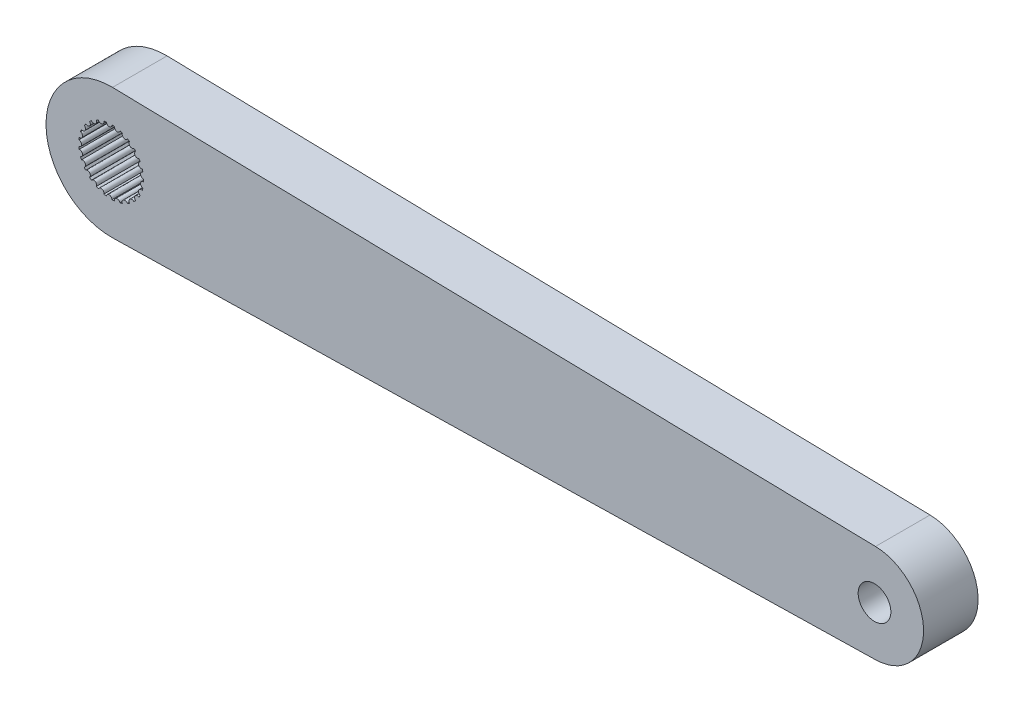
SolidWorks part; units mm, degrees
ref_plane "Plan de face" through (0, 0, 0) normal (0, 0, 1) x (1, 0, 0)
ref_plane "Plan de dessus" through (0, 0, 0) normal (0, 1, 0) x (1, 0, 0)
ref_plane "Plan de droite" through (0, 0, 0) normal (1, 0, 0) x (0, 0, -1)
sketch "Esquisse1" plane through (0, 0, 0) normal (0, 0, 1) x (1, 0, 0)
  line L0 (0.1259, 5.9737) -> (70.0948, 4.499)
  line L1 (0.1259, -5.9737) -> (70.0948, -4.499)
  line L2 (70, 0) -> (0, 0) construction
  circle A0 centre (0, 0) radius 2.975
  circle A1 centre (70, 0) radius 1.5
  arc A2 (0.1259, 5.9737) -> (0.1259, -5.9737) centre (0, 0) ccw
  arc A3 (70.0948, -4.499) -> (70.0948, 4.499) centre (70, 0) ccw
  dimension "D1" = 5.95
  dimension "D2" = 3
  dimension "D4" = 3
  dimension "D5" = 3
  dimension "D3" = 70
extrude "Boss.-Extru.1" add sketch "Esquisse1" along normal blind 5
sketch "Esquisse2" plane through (0, 0, 5) normal (0, 0, 1) x (1, 0, 0)
  line L0 (0, 0) -> (3.8884, 0) construction
  line L1 (0, 0) -> (2.9515, 0.3729) construction
  circle A0 centre (2.9515, 0.3729) radius 0.26
  circle A1 centre (0, 0) radius 2.975 construction
  circle A2 centre (2.9515, -0.3729) radius 0.26
  circle A3 centre (2.7661, -1.0952) radius 0.26
  circle A4 centre (2.4068, -1.7487) radius 0.26
  circle A5 centre (1.8963, -2.2923) radius 0.26
  circle A6 centre (1.2667, -2.6919) radius 0.26
  circle A7 centre (0.5575, -2.9223) radius 0.26
  circle A8 centre (-0.1868, -2.9691) radius 0.26
  circle A9 centre (-0.9193, -2.8294) radius 0.26
  circle A10 centre (-1.5941, -2.5119) radius 0.26
  circle A11 centre (-2.1687, -2.0365) radius 0.26
  circle A12 centre (-2.607, -1.4332) radius 0.26
  circle A13 centre (-2.8815, -0.7399) radius 0.26
  circle A14 centre (-2.975, 0) radius 0.26
  circle A15 centre (-2.8815, 0.7399) radius 0.26
  circle A16 centre (-2.607, 1.4332) radius 0.26
  circle A17 centre (-2.1687, 2.0365) radius 0.26
  circle A18 centre (-1.5941, 2.5119) radius 0.26
  circle A19 centre (-0.9193, 2.8294) radius 0.26
  circle A20 centre (-0.1868, 2.9691) radius 0.26
  circle A21 centre (0.5575, 2.9223) radius 0.26
  circle A22 centre (1.2667, 2.6919) radius 0.26
  circle A23 centre (1.8963, 2.2923) radius 0.26
  circle A24 centre (2.4068, 1.7487) radius 0.26
  circle A25 centre (2.7661, 1.0952) radius 0.26
  point P54 (0, 0)
  dimension "D1" = 0.52
  dimension "D3" = 7.2
  dimension "D2" = 25
extrude "Boss.-Extru.2" add sketch "Esquisse2" against normal up to surface (5 mm away) up to face at (34.6864, 0, 0)
sketch "Esquisse3" plane through (0, 0, 5) normal (0, 0, 1) x (1, 0, 0)
  line L0 (0, 0) -> (70, 0) construction
